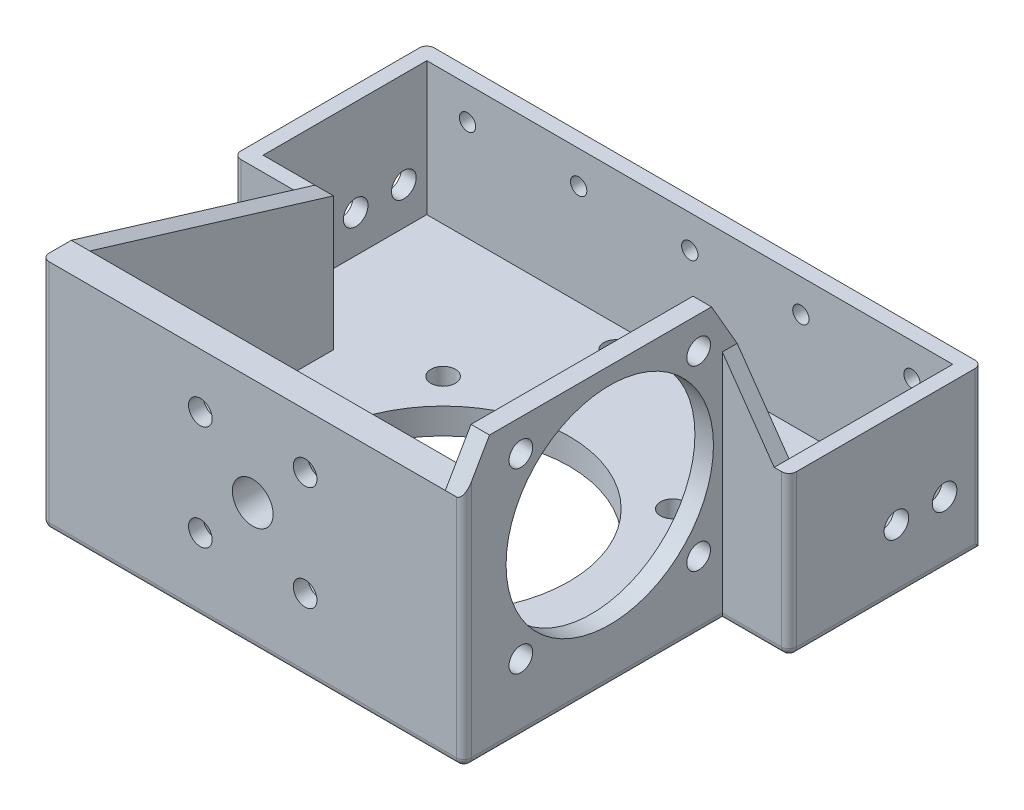
SolidWorks part; units mm, degrees
ref_plane "前视基准面" through (0, 0, 0) normal (0, 0, 1) x (1, 0, 0)
ref_plane "上视基准面" through (0, 0, 0) normal (0, 1, 0) x (1, 0, 0)
ref_plane "右视基准面" through (0, 0, 0) normal (1, 0, 0) x (0, 0, -1)
sketch "草图2" plane through (0, 0, 0) normal (0, 1, 0) x (1, 0, 0)
  line L15 (-9, 34.9) -> (-9, 61)
  line L16 (-9, 61) -> (6, 61)
  line L20 (6, 61) -> (51, 61)
  line L24 (51, 61) -> (66, 61)
  line L25 (66, 61) -> (66, 34.9)
  line L27 (-9, 34.9) -> (0, 34.9)
  line L28 (0, 34.9) -> (0, 0)
  line L29 (0, 0) -> (57, 0)
  line L30 (57, 0) -> (57, 34.9)
  line L31 (57, 34.9) -> (66, 34.9)
  line L32 (28.5, -43.9837) -> (28.5, 74.5213) construction
  circle A6 centre (21.5, 56) radius 1.6
  circle A7 centre (35.5, 56) radius 1.6
  circle A10 centre (28.5, 25.7) radius 17
  circle A11 centre (44, 41.2) radius 1.65
  circle A12 centre (44, 10.2) radius 1.65
  circle A13 centre (13, 10.2) radius 1.65
  circle A14 centre (13, 41.2) radius 1.65
  point P0 (-1.5, 56)
  point P1 (58.5, 56)
  point P6 (21.5, 56)
  point P50 (28.5, 25.7)
  dimension "D20" = 3.2
  dimension "D22" = 34
  dimension "D7" = 25.7
  dimension "D10" = 57
  dimension "D11" = 61
  dimension "D14" = 3.3
  dimension "D17" = 31
  dimension "D3" = 26.1
  dimension "D4" = 14
  dimension "D5" = 5
  dimension "D6" = 28.5
  dimension "D8" = 75
  dimension "D16" = 4
  dimension "D19" = 28.5
extrude "凸台-拉伸2" add sketch "草图2" along normal blind 3.5
sketch "草图6" plane through (0, 3.5, 0) normal (0, 1, 0) x (1, 0, 0)
  line L9 (28.5, 25.7) -> (28.5, -10.253) construction
  line L14 (66, 61) -> (-9, 61) construction
  line L19 (66, 34.9) -> (66, 61) construction
  line L20 (57, 34.9) -> (66, 34.9) construction
  line L21 (57, 0) -> (57, 34.9) construction
  line L22 (0, 0) -> (57, 0) construction
  line L23 (0, 34.9) -> (0, 0) construction
  line L24 (-9, 34.9) -> (0, 34.9) construction
  line L30 (66, 61) -> (-9, 61)
  line L35 (66, 34.9) -> (66, 61)
  line L36 (57, 34.9) -> (66, 34.9)
  line L37 (57, 0) -> (57, 34.9)
  line L38 (0, 0) -> (57, 0)
  line L39 (0, 34.9) -> (0, 0)
  line L40 (-9, 34.9) -> (0, 34.9)
  line L41 (-9, 61) -> (-9, 34.9)
  line L46 (15.5, 59) -> (-7, 59)
  line L47 (-7, 59) -> (-7, 36.9)
  line L48 (-7, 36.9) -> (2.5, 36.9)
  line L49 (2.5, 36.9) -> (2.5, 4)
  line L50 (2.5, 4) -> (54.5, 4)
  line L51 (54.5, 4) -> (54.5, 36.9)
  line L52 (54.5, 36.9) -> (64, 36.9)
  line L53 (64, 36.9) -> (64, 59)
  line L54 (64, 59) -> (41.5, 59)
  line L58 (41.5, 59) -> (15.5, 59)
  dimension "D1" = 4
  dimension "D2" = 2
  dimension "D5" = 2
  dimension "D7" = 2
  dimension "D12" = 2
  dimension "D13" = 2
  dimension "D14" = 2.5
  dimension "D15" = 2.5
extrude "凸台-拉伸3" add sketch "草图6" along normal blind 18
sketch "草图11" plane through (0, 21.5, 0) normal (0, 1, 0) x (1, 0, 0)
  line L0 (2.5, 36.9) -> (2.5, 4)
  line L1 (2.5, 4) -> (54.5, 4)
  line L2 (54.5, 4) -> (54.5, 36.9)
  line L3 (54.5, 36.9) -> (57, 36.9)
  line L4 (54.5, 36.9) -> (64, 36.9) construction
  line L5 (57, 36.9) -> (57, 0)
  line L6 (57, 0) -> (57, 34.9) construction
  line L7 (57, 0) -> (0, 0)
  line L8 (0, 0) -> (0, 36.9)
  line L9 (-7, 36.9) -> (2.5, 36.9) construction
  line L10 (0, 36.9) -> (2.5, 36.9)
extrude "凸台-拉伸4" add sketch "草图11" along normal blind 10
sketch "草图12" plane through (0, 0, 0) normal (-1, 0, 0) x (0, 0, 1)
  line L0 (-36.9, 21.5) -> (-4, 31.5)
  line L1 (-36.9, 31.5) -> (0, 31.5) construction
  line L2 (-4, 31.5) -> (-36.9, 31.5)
  line L3 (-36.9, 31.5) -> (-36.9, 21.5)
  line L4 (0, 31.5) -> (0, 0) construction
  dimension "D1" = 4
extrude "切除-拉伸5" cut sketch "草图12" against normal blind 3
sketch "草图10" plane through (0, 0, 0) normal (0, 0, 1) x (1, 0, 0)
  line L0 (28.5, 37.2917) -> (28.5, -8.8083) construction
  line L5 (0, 0) -> (57, 0) construction
  line L6 (0, 31.5) -> (0, 0) construction
  line L7 (57, 31.5) -> (57, 0) construction
  circle A0 centre (28.5, 17.0711) radius 2.75
  circle A1 centre (35.5711, 24.1421) radius 1.6
  circle A2 centre (35.5711, 10) radius 1.6
  circle A3 centre (21.4289, 10) radius 1.6
  circle A4 centre (21.4289, 24.1421) radius 1.6
  point P19 (28.5, 17.0711)
  dimension "D1" = 10
  dimension "D2" = 5.5
  dimension "D3" = 3.2
  dimension "D4" = 10
  dimension "D5" = 4
extrude "切除-拉伸4" cut sketch "草图10" against normal blind 5
sketch "草图14" plane through (0, 0, -61) normal (0, 0, -1) x (-1, 0, 0)
  line L0 (-28.5, 46.072) -> (-28.5, -18.623) construction
  line L1 (9, 21.5) -> (9, 0) construction
  line L2 (-66, 21.5) -> (-66, 0) construction
  line L3 (-28.5, 17.0711) -> (13.7995, 17.0711) construction
  circle A0 centre (31.5, 17.0711) radius 1.55
  circle A1 centre (-88.5, 17.0711) radius 1.55
  circle A2 centre (-28.5, 17.0711) radius 1.1
  circle A5 centre (-13.5, 17.0711) radius 1.1
  circle A6 centre (1.5, 17.0711) radius 1.1
  circle A7 centre (-43.5, 17.0711) radius 1.1
  circle A8 centre (-58.5, 17.0711) radius 1.1
  dimension "D1" = 3.1
  dimension "D2" = 120
  dimension "D3" = 3
  dimension "D4" = 2.2
  dimension "D5" = 3
extrude "切除-拉伸6" cut sketch "草图14" against normal blind 10
sketch "草图16" plane through (0, 0, 0) normal (-1, 0, 0) x (0, 0, 1)
  line L0 (-20.9, 26.3632) -> (-20.9, 18.5)
  line L1 (-36.9, 21.5) -> (-4, 31.5) construction
  line L2 (-20.9, 18.5) -> (-36.9, 18.5)
  line L3 (-36.9, 21.5) -> (-36.9, 18.5)
  line L4 (-36.9, 21.5) -> (-20.9, 26.3632)
  dimension "D1" = 16
  dimension "D2" = 3
sketch "草图20" plane through (0, 0, -4) normal (0, 0, -1) x (-1, 0, 0)
  line L0 (-24.4289, 22.4101) -> (-21.4289, 20.678)
  line L1 (-33.839, 21.1421) -> (-32.107, 24.1421)
  line L2 (-32.107, 24.1421) -> (-33.839, 27.1421)
  line L3 (-33.839, 27.1421) -> (-37.3031, 27.1421)
  line L4 (-37.3031, 27.1421) -> (-39.0352, 24.1421)
  line L5 (-39.0352, 24.1421) -> (-37.3031, 21.1421)
  line L6 (-37.3031, 21.1421) -> (-33.839, 21.1421)
  line L7 (-21.4289, 20.678) -> (-18.4289, 22.4101)
  line L8 (-18.4289, 22.4101) -> (-18.4289, 25.8742)
  line L9 (-18.4289, 25.8742) -> (-21.4289, 27.6062)
  line L10 (-21.4289, 27.6062) -> (-24.4289, 25.8742)
  line L11 (-24.4289, 25.8742) -> (-24.4289, 22.4101)
  line L12 (-23.161, 13) -> (-24.893, 10)
  line L13 (-24.893, 10) -> (-23.161, 7)
  line L14 (-23.161, 7) -> (-19.6969, 7)
  line L15 (-19.6969, 7) -> (-17.9648, 10)
  line L16 (-17.9648, 10) -> (-19.6969, 13)
  line L17 (-19.6969, 13) -> (-23.161, 13)
  line L18 (-32.5711, 11.7321) -> (-35.5711, 13.4641)
  line L19 (-35.5711, 13.4641) -> (-38.5711, 11.7321)
  line L20 (-38.5711, 11.7321) -> (-38.5711, 8.2679)
  line L21 (-38.5711, 8.2679) -> (-35.5711, 6.5359)
  line L22 (-35.5711, 6.5359) -> (-32.5711, 8.2679)
  line L23 (-32.5711, 8.2679) -> (-32.5711, 11.7321)
  circle A0 centre (-35.5711, 24.1421) radius 3 construction
  point P30 (-28.5, 17.0711)
  dimension "D1" = 6
  dimension "D2" = 4
extrude "切除-拉伸7" cut sketch "草图20" against normal blind 2
sketch "草图22" plane through (0, 0, -36.9) normal (0, 0, -1) x (-1, 0, 0)
  line L0 (-57, 31.5) -> (-64.0021, 21.5)
  line L2 (-64.0021, 21.5) -> (-57, 21.5)
  line L3 (-57, 21.5) -> (-57, 31.5)
  dimension "D1" = 35
extrude "凸台-拉伸6" add sketch "草图22" against normal up to surface (2 mm away) up to face at (61.5, 10.75, -34.9)
sketch "草图24" plane through (57, 0, 0) normal (1, 0, 0) x (0, 0, -1)
  line L0 (0, 31.5) -> (3.4641, 37.5)
  line L1 (3.4641, 37.5) -> (33.4359, 37.5)
  line L2 (33.4359, 37.5) -> (36.9, 31.5)
  line L3 (36.9, 31.5) -> (36.9, 21.5) construction
  line L4 (0, 31.5) -> (34.9, 31.5) construction
  line L5 (0, 31.5) -> (34.9, 31.5) construction
  line L6 (36.9, 31.5) -> (0, 31.5)
  dimension "D1" = 60
  dimension "D2" = 60
  dimension "D3" = 6
extrude "凸台-拉伸7" add sketch "草图24" against normal up to surface (2.5 mm away) up to face at (54.5, 17.5, -20.45)
sketch "草图21" plane through (57, 0, 0) normal (1, 0, 0) x (0, 0, -1)
  circle A8 centre (7.7, 33.2) radius 1.6
  circle A9 centre (31.7, 33.2) radius 1.6
  circle A10 centre (31.7, 9.2) radius 1.6
  circle A11 centre (7.7, 9.2) radius 1.6
  circle A12 centre (19.7, 21.2) radius 14
  dimension "D1" = 3.2
  dimension "D2" = 28
extrude "切除-拉伸8" cut sketch "草图21" against normal blind 3
fillet "圆角1" radius 1 14 edges at (57, 15.75, 0) (57, 0, -17.45) (61.5, 0, -34.9) (66, 0, -47.95) (0, 15.75, 0) (0, 0, -17.45) (28.5, 0, 0) (0, 10.75, -34.9) (-9, 10.75, -34.9) (-4.5, 0, -34.9) (-9, 0, -47.95) (-9, 10.75, -61) (66, 10.75, -61) (66, 10.75, -34.9)
sketch "草图25" plane through (66, 0, 0) normal (1, 0, 0) x (0, 0, -1)
  line L0 (61, 21.5) -> (61, 0) construction
  line L1 (61, 0) -> (35.9, 0) construction
  circle A0 centre (55.9, 8.56) radius 1.6612
  circle A2 centre (49.4, 8.56) radius 1.6612
  dimension "D1" = 5.1
  dimension "D2" = 3.3224
  dimension "D3" = 8.56
  dimension "D4" = 6.5
extrude "切除-拉伸9" cut sketch "草图25" against normal blind 10
sketch "草图27" plane through (-9, 0, 0) normal (-1, 0, 0) x (0, 0, 1)
  circle A0 centre (-55.9, 8.56) radius 1.6612
  circle A1 centre (-49.4, 8.56) radius 1.6612
extrude "切除-拉伸10" cut sketch "草图27" against normal blind 10
